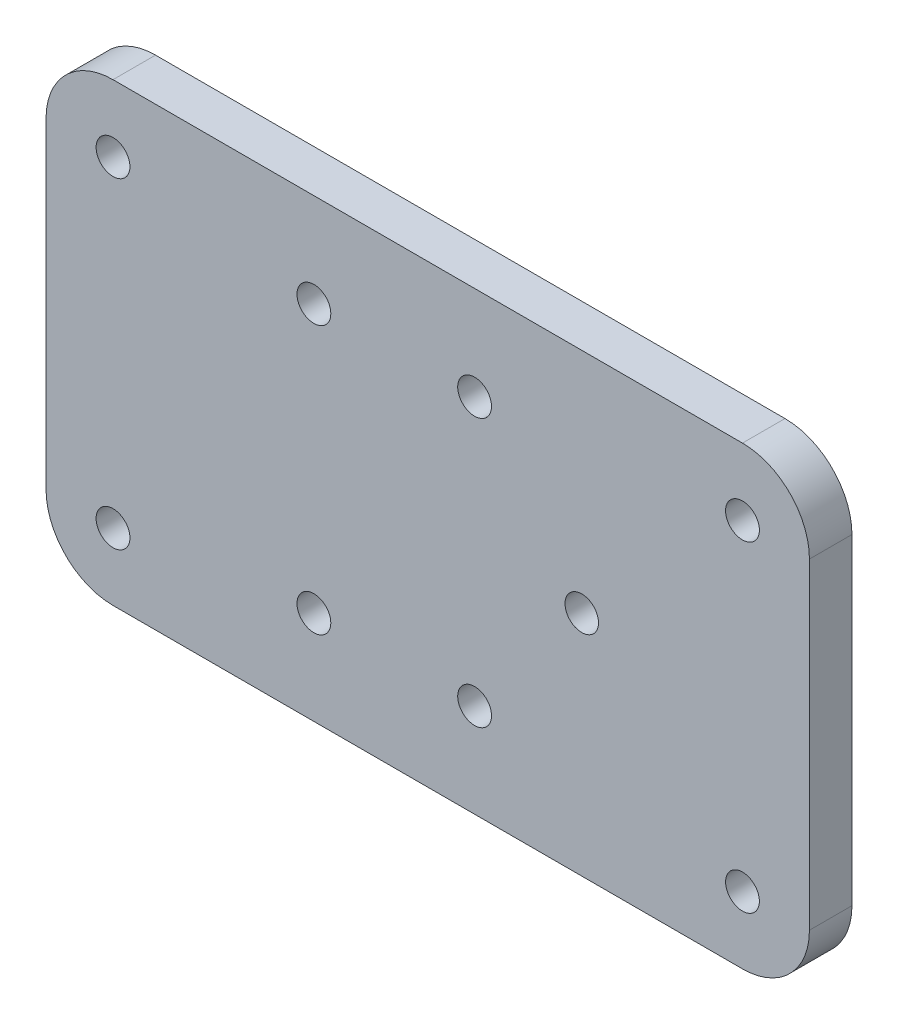
SolidWorks part; units mm, degrees
ref_plane "Front Plane" through (0, 0, 0) normal (0, 0, 1) x (1, 0, 0)
ref_plane "Top Plane" through (0, 0, 0) normal (0, 1, 0) x (1, 0, 0)
ref_plane "Right Plane" through (0, 0, 0) normal (1, 0, 0) x (0, 0, -1)
sketch "Sketch1" plane through (0, 0, 0) normal (0, 0, 1) x (1, 0, 0)
  line L0 (-47, 34) -> (47, 34)
  line L1 (-47, 24) -> (47, 24) construction
  line L2 (-47, 24) -> (-47, -24) construction
  line L3 (-47, -24) -> (47, -24) construction
  line L4 (47, 24) -> (47, -24) construction
  line L5 (0, -24) -> (0, 24) construction
  line L6 (-47, 0) -> (47, 0) construction
  line L7 (57, 24) -> (57, -24)
  line L8 (-47, -34) -> (47, -34)
  line L9 (-57, 24) -> (-57, -24)
  line L10 (-57, 34) -> (57, 34) construction
  line L11 (-57, 34) -> (-57, -34) construction
  line L12 (57, 34) -> (57, -34) construction
  line L13 (-57, -34) -> (57, -34) construction
  line L15 (7, -20) -> (-17, -20) construction
  line L16 (7, -20) -> (7, 20) construction
  line L17 (7, 20) -> (-17, 20) construction
  line L18 (-17, -20) -> (-17, 20) construction
  line L19 (-5, 20) -> (-5, -20) construction
  line L20 (7, 0) -> (-17, 0) construction
  circle A0 centre (-47, -24) radius 2.525
  circle A1 centre (47, -24) radius 2.525
  circle A2 centre (47, 24) radius 2.525
  circle A3 centre (-47, 24) radius 2.525
  arc A4 (-47, 34) -> (-57, 24) centre (-47, 24) ccw
  arc A5 (57, 24) -> (47, 34) centre (47, 24) ccw
  arc A6 (-57, -24) -> (-47, -34) centre (-47, -24) ccw
  arc A7 (47, -34) -> (57, -24) centre (47, -24) ccw
  circle A8 centre (-17, 20) radius 2.525
  circle A9 centre (-17, -20) radius 2.525
  circle A10 centre (7, 20) radius 2.525
  circle A11 centre (7, -20) radius 2.525
  circle A12 centre (23, 0) radius 2.5
  point P0 (-5, 0)
  point P171 (0, 0)
  dimension "D1" = 94
  dimension "D2" = 48
  dimension "D3" = 5.05
  dimension "D5" = 24
  dimension "D6" = 40
  dimension "D8" = 40
  dimension "D9" = 5
  dimension "D4" = 10
  dimension "D7" = 30
extrude "Boss-Extrude1" add sketch "Sketch1" along normal blind 6.35
sketch "Sketch2" plane through (0, 0, 0) normal (0, 0, -1) x (-1, 0, 0)
  line L1 (-28, -27) -> (26, -27)
  line L2 (-28, -27) -> (-28, 27)
  line L3 (-28, 27) -> (26, 27)
  line L4 (26, -27) -> (26, 27)
  line L5 (-1, 27) -> (-1, -27) construction
  line L6 (-28, 0) -> (26, 0) construction
  circle A0 centre (17, 20) radius 2.525 construction
  point P0 (-1, 0)
  dimension "D3" = 9
  dimension "D1" = 54
  dimension "D2" = 54
extrude "Cut-Extrude1" cut sketch "Sketch2" against normal blind 2.3
sketch "Sketch3" plane through (0, 0, 2.3) normal (0, 0, -1) x (-1, 0, 0)
  line L0 (-28, 27) -> (-25.8787, 24.8787) construction
  line L1 (-28, 27) -> (-25.8787, 27) construction
  line L2 (26, 27) -> (-28, 27) construction
  line L3 (-25.8787, 27) -> (-25.8787, 24.8787) construction
  line L4 (26, 27) -> (-28, 27) construction
  line L6 (-28, 27) -> (-28, -27) construction
  line L7 (-25.8787, 27) -> (-28, 27) construction
  line L8 (-22.4832, 27) -> (-22.4832, 21.4832)
  line L9 (-22.4832, 21.4832) -> (-28, 21.4832)
  line L10 (-28, 27) -> (-28, -27) construction
  line L11 (-1, 0) -> (-1, 27) construction
  line L12 (-1, 0) -> (-28, 0) construction
  line L13 (23.8787, 27) -> (26, 27) construction
  line L14 (23.8787, 27) -> (23.8787, 24.8787) construction
  line L15 (26, 27) -> (23.8787, 27) construction
  line L16 (26, 27) -> (23.8787, 24.8787) construction
  line L17 (20.4832, 21.4832) -> (26, 21.4832)
  line L18 (20.4832, 27) -> (20.4832, 21.4832)
  line L19 (26, -27) -> (23.8787, -24.8787) construction
  line L20 (26, -27) -> (23.8787, -27) construction
  line L21 (23.8787, -27) -> (23.8787, -24.8787) construction
  line L22 (23.8787, -27) -> (26, -27) construction
  line L23 (-25.8787, -27) -> (-28, -27) construction
  line L24 (-25.8787, -27) -> (-25.8787, -24.8787) construction
  line L25 (-28, -27) -> (-25.8787, -27) construction
  line L26 (-28, -27) -> (-25.8787, -24.8787) construction
  line L27 (20.4832, -27) -> (20.4832, -21.4832)
  line L28 (20.4832, -21.4832) -> (26, -21.4832)
  line L29 (-22.4832, -21.4832) -> (-28, -21.4832)
  line L30 (-22.4832, -27) -> (-22.4832, -21.4832)
  arc A4 (-24.4235, 27.5021) -> (-28.5021, 23.4235) centre (-25.8787, 24.8787) ccw
  arc A5 (-24.4235, 27.5021) -> (-22.4832, 27) centre (-22.4832, 31) ccw
  arc A6 (-28.5021, 23.4235) -> (-28, 21.4832) centre (-32, 21.4832) cw
  arc A7 (26.5021, 23.4235) -> (26, 21.4832) centre (30, 21.4832) ccw
  arc A8 (22.4235, 27.5021) -> (20.4832, 27) centre (20.4832, 31) cw
  arc A9 (22.4235, 27.5021) -> (26.5021, 23.4235) centre (23.8787, 24.8787) cw
  arc A10 (22.4235, -27.5021) -> (26.5021, -23.4235) centre (23.8787, -24.8787) ccw
  arc A11 (22.4235, -27.5021) -> (20.4832, -27) centre (20.4832, -31) ccw
  arc A12 (26.5021, -23.4235) -> (26, -21.4832) centre (30, -21.4832) cw
  arc A13 (-28.5021, -23.4235) -> (-28, -21.4832) centre (-32, -21.4832) ccw
  arc A14 (-24.4235, -27.5021) -> (-22.4832, -27) centre (-22.4832, -31) cw
  arc A15 (-24.4235, -27.5021) -> (-28.5021, -23.4235) centre (-25.8787, -24.8787) cw
  dimension "D1" = 6
  dimension "D3" = 4
  dimension "D4" = 4
  dimension "D2" = 45
extrude "Cut-Extrude2" cut sketch "Sketch3" along normal up to surface (2.3 mm away) up to face at (1, 0, 0)
